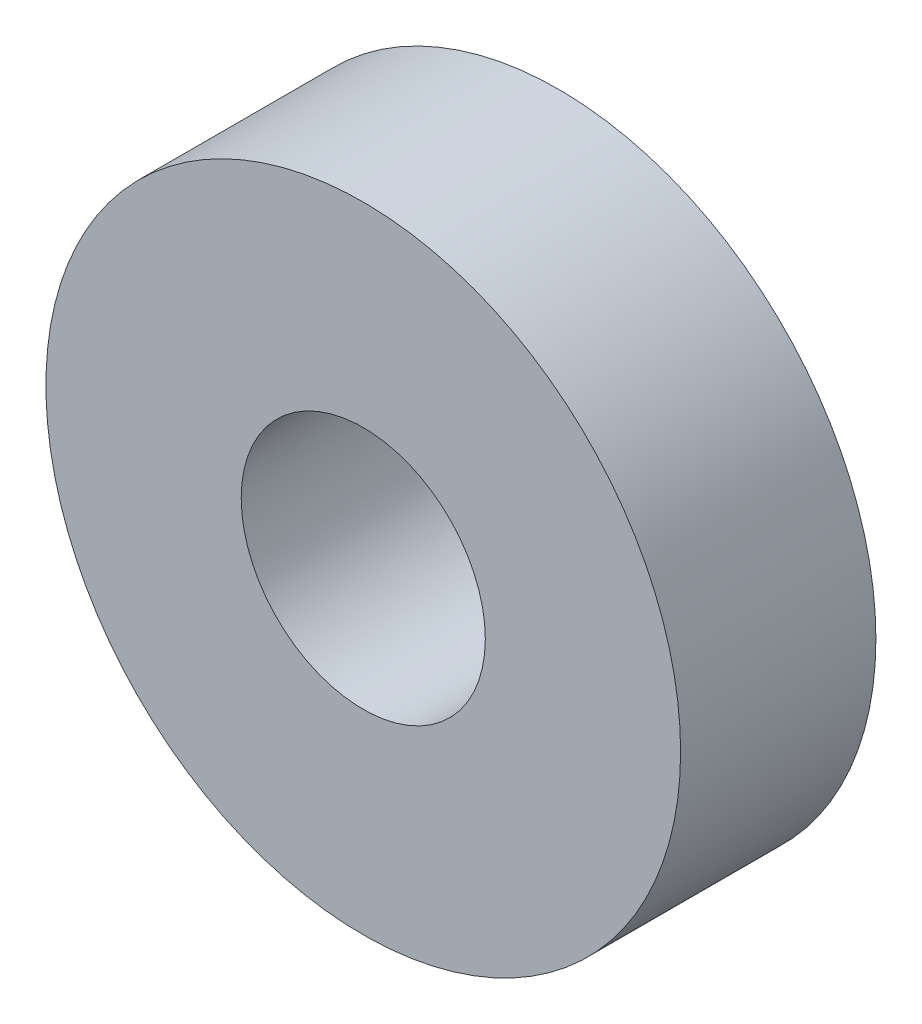
SolidWorks part; units mm, degrees
ref_plane "Спереди" through (0, 0, 0) normal (0, 0, 1) x (1, 0, 0)
ref_plane "Сверху" through (0, 0, 0) normal (0, 1, 0) x (1, 0, 0)
ref_plane "Справа" through (0, 0, 0) normal (1, 0, 0) x (0, 0, -1)
sketch "Эскиз4" plane through (0, 0, 0) normal (0, 0, 1) x (1, 0, 0)
  circle A0 centre (0, 0) radius 3.25
  circle A1 centre (0, 0) radius 1.25
  dimension "D1" = 2.5
  dimension "D2" = 2
extrude "Бобышка-Вытянуть2" add sketch "Эскиз4" along normal blind 2
